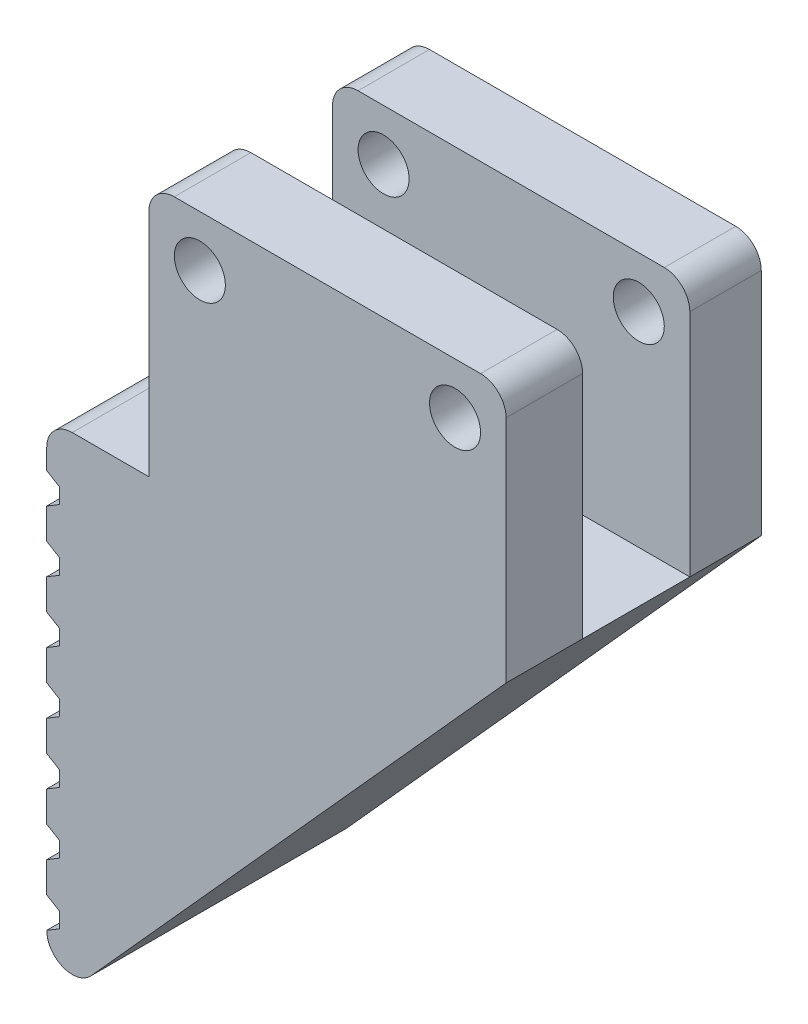
SolidWorks part; units mm, degrees
ref_plane "前视基准面" through (0, 0, 0) normal (0, 0, 1) x (1, 0, 0)
ref_plane "上视基准面" through (0, 0, 0) normal (0, 1, 0) x (1, 0, 0)
ref_plane "右视基准面" through (0, 0, 0) normal (1, 0, 0) x (0, 0, -1)
sketch "草图1" plane through (0, 0, 0) normal (0, 0, 1) x (1, 0, 0)
  line L0 (7, -5) -> (-11, -25)
  line L1 (-7, 5) -> (7, 5)
  line L2 (-7, 5) -> (-7, -5)
  line L3 (-7, -5) -> (7, -5)
  line L4 (7, 5) -> (7, -5)
  line L5 (-7, 5) -> (7, -5) construction
  line L6 (-7, -5) -> (7, 5) construction
  line L7 (-11, -25) -> (-11, -5)
  line L8 (-11, -5) -> (-7, -5)
  point P0 (0, 0)
  dimension "D1" = 14
  dimension "D2" = 10
  dimension "D3" = 20
  dimension "D4" = 18
extrude "凸台-拉伸1" add sketch "草图1" along normal blind 10 contours L4 L1 L2 L3 | L8 L7 L0 L3
sketch "草图2" plane through (0, 0, 10) normal (0, 0, 1) x (1, 0, 0)
  line L0 (-7, 5) -> (-7, -5) construction
  line L1 (-7, 5) -> (7, 5) construction
  circle A0 centre (-5, 3) radius 1
  circle A1 centre (5, 3) radius 1
  dimension "D1" = 10
  dimension "D2" = 2
  dimension "D3" = 2
  dimension "D4" = 2
  dimension "D5" = 2
extrude "切除-拉伸1" cut sketch "草图2" against normal blind 10
sketch "草图3" plane through (0, 5, 0) normal (0, 1, 0) x (1, 0, 0)
  line L0 (-7, -10) -> (-7, 0) construction
  line L1 (-7, -2.8) -> (7, -2.8)
  line L2 (-7, -2.8) -> (-7, -7)
  line L3 (-7, -7) -> (7, -7)
  line L4 (7, -2.8) -> (7, -7)
  line L5 (7, -10) -> (7, 0) construction
  line L6 (-7, -10) -> (7, -10) construction
  dimension "D1" = 4.2
  dimension "D2" = 3
extrude "切除-拉伸2" cut sketch "草图3" against normal blind 10
fillet "圆角1" radius 1 2 edges at (-11, -25, 5) (-11, -5, 5)
sketch "草图5" plane through (0, 0, 10) normal (0, 0, 1) x (1, 0, 0)
  line L0 (-11, -22.394) -> (-10.5, -22.094)
  line L1 (-10.5, -22.094) -> (-10.5, -21.494)
  line L2 (-10.5, -21.494) -> (-11, -21.194)
  line L3 (-11, -22.394) -> (-11, -6) construction
  dimension "D1" = 1.2
  dimension "D2" = 0.6
  dimension "D3" = 0.3
  dimension "D4" = 0.5
extrude "切除-拉伸3" cut sketch "草图5" against normal blind 10 and the other way through all
pattern_linear "阵列(线性)1" count 7 spacing 2.4 along (0, 1, 0) of "切除-拉伸3"
fillet "圆角2" radius 1 4 edges at (-7, 5, 8.5) (-7, 5, 1.4) (7, 5, 1.4) (7, 5, 8.5)
